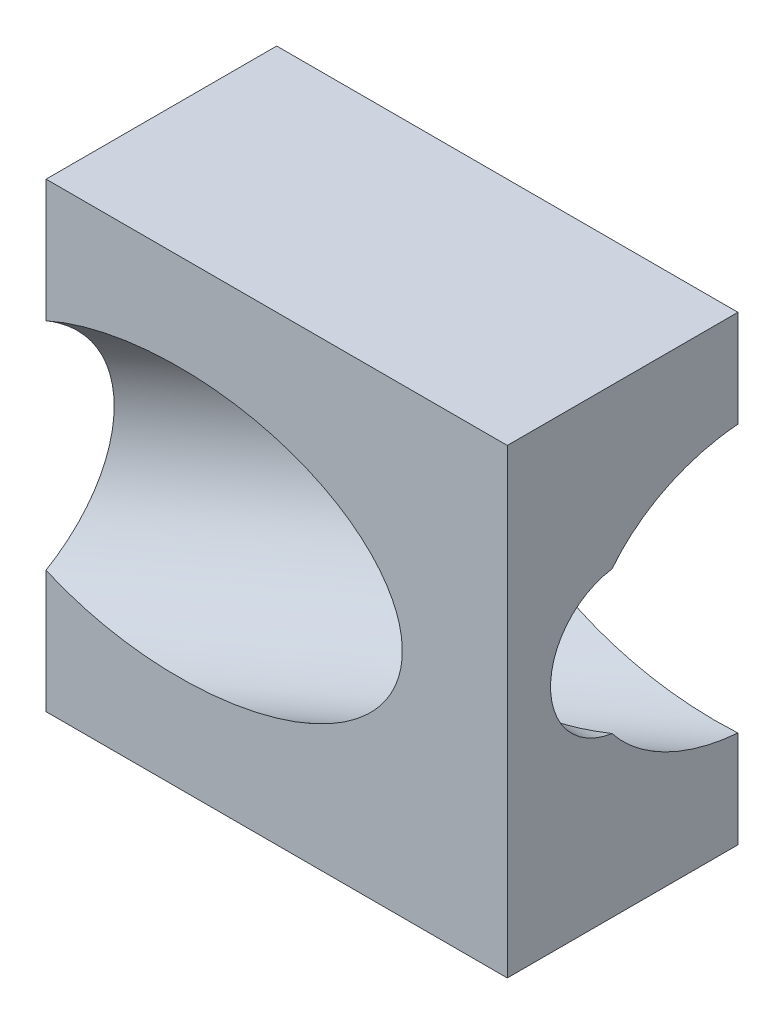
SolidWorks part; units mm, degrees
ref_plane "Front Plane" through (0, 0, 0) normal (0, 0, 1) x (1, 0, 0)
ref_plane "Top Plane" through (0, 0, 0) normal (0, 1, 0) x (1, 0, 0)
ref_plane "Right Plane" through (0, 0, 0) normal (1, 0, 0) x (0, 0, -1)
sketch "Sketch1" plane through (0, 0, 0) normal (0, 0, 1) x (1, 0, 0)
  line L0 (0, 0) -> (50.8, 50.8) construction
  line L1 (0, 0) -> (50.8, 0)
  line L2 (0, 0) -> (0, 50.8)
  line L3 (0, 50.8) -> (50.8, 50.8)
  line L4 (50.8, 0) -> (50.8, 50.8)
  circle A0 centre (9.6846, 9.6846) radius 6.35 construction
  circle A1 centre (41.1154, 41.1154) radius 6.35 construction
  circle A2 centre (25.4, 25.4) radius 22.225 construction
  dimension "D2" = 44.45
  dimension "D3" = 12.7
  dimension "D1" = 50.8
extrude "Boss-Extrude1" add sketch "Sketch1" along normal blind 25.4
sketch "Sketch2" plane through (50.8, 0, 0) normal (1, 0, 0) x (0, 0, -1)
  line L0 (-25.4, 50.8) -> (0, 0) construction
  circle A0 centre (-12.7, 25.4) radius 7.9375
  dimension "D1" = 15.875
extrude "Cut-Extrude1" cut sketch "Sketch2" against normal blind 25.4
sketch "Sketch3" plane through (0, 0, 25.4) normal (0, 0, 1) x (1, 0, 0)
  line L0 (50.8, 25.4) -> (-49.1182, 25.4)
  line L1 (50.8, 0) -> (50.8, 50.8) construction
  line L2 (-49.1182, 25.4) -> (-49.1182, 47.186)
ref_plane "Plane1" through (0, 0, 7.62) normal (0, 0, 1) x (1, 0, 0)
ref_plane "Plane2" through (25.4, 0, 0) normal (1, 0, 0) x (0, 0, -1)
ref_plane "Plane3" through (10.16, 0, 20.32) normal (-0.4472, 0, -0.8944) x (-0.8944, 0, 0.4472)
ref_plane "Plane4" through (-43.5365, 0, 32.8071) normal (-0.7986, 0, 0.6018) x (0, 1, 0)
sketch "Sketch4" plane through (-43.5365, 0, 32.8071) normal (-0.7986, 0, 0.6018) x (0, 1, 0)
  line L0 (25.4, -50.8575) -> (25.4, 9.2747) construction
  circle A0 centre (25.4, -29.0976) radius 14.8017
extrude "Cut-Extrude2" cut sketch "Sketch4" against normal through all
